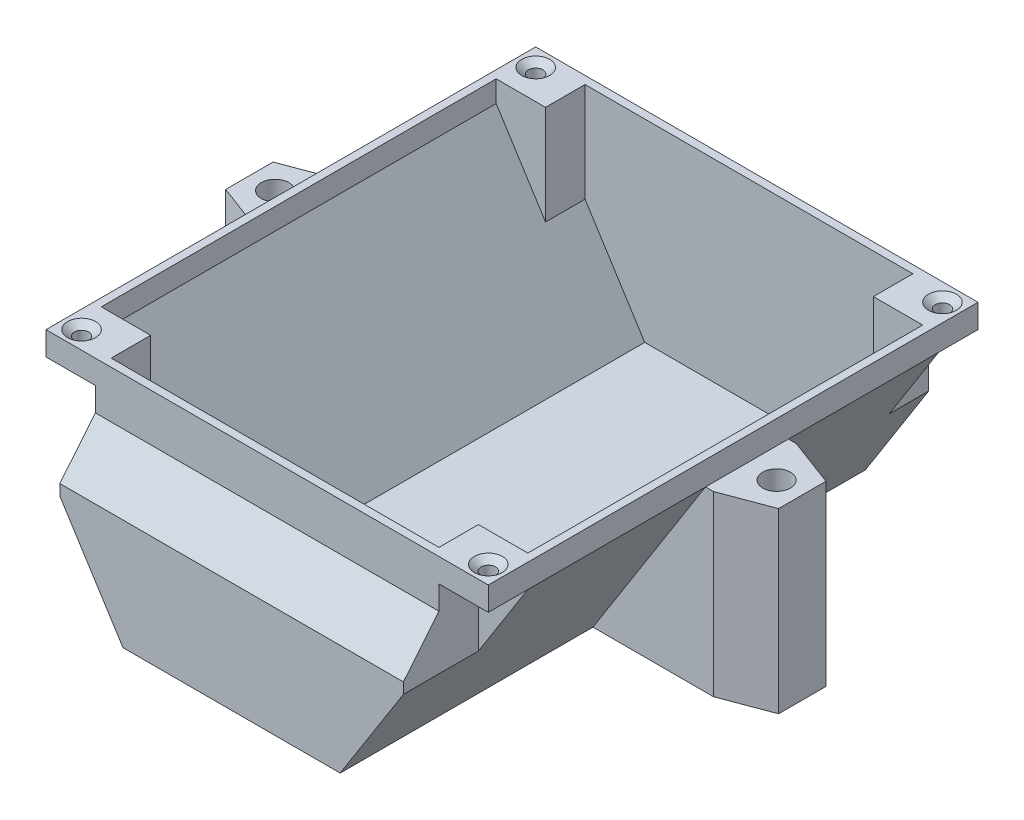
SolidWorks part; units mm, degrees
ref_plane "Front Plane" through (0, 0, 0) normal (0, 0, 1) x (1, 0, 0)
ref_plane "Top Plane" through (0, 0, 0) normal (0, 1, 0) x (1, 0, 0)
ref_plane "Right Plane" through (0, 0, 0) normal (1, 0, 0) x (0, 0, -1)
sketch "Front face" plane through (0, 0, 0) normal (0, 0, 1) x (1, 0, 0)
  line L0 (-28.5, 45) -> (83.5, 45)
  line L1 (0, 0) -> (55, 0)
  line L2 (83.5, 45) -> (55, 0)
  line L3 (-28.5, 45) -> (0, 0)
  line L4 (27.5, 0) -> (27.5, 45) construction
  dimension "D1" = 112
  dimension "D2" = 45
extrude "Main Body" add sketch "Front face" along normal blind 124 contours L2 L1 L3 L0
sketch "Sketch38" plane through (0, 45, 0) normal (0, 1, 0) x (1, 0, 0)
  line L0 (83.5, 0) -> (83.5, -124)
  line L1 (83.5, -124) -> (-28.5, -124)
  line L2 (-28.5, -124) -> (-28.5, 0)
  line L3 (-28.5, 0) -> (83.5, 0)
extrude "Boss-Extrude2" add sketch "Sketch38" along normal blind 6
sketch3d "Reference perpendicular"
  line L1 (0, 0, 0) -> (55, 0, 0) construction
sketch "Sketch22" plane through (0, 51, 0) normal (0, 1, 0) x (1, 0, 0)
  line L0 (-28.5, 0) -> (-16.0038, 0)
  line L1 (-28.5, 0) -> (83.5, 0) construction
  line L2 (-16.0038, 0) -> (-16.0038, -10)
  line L3 (-16.0038, -10) -> (-28.5, -10)
  line L5 (-28.5, -10) -> (-28.5, 0)
  line L6 (-28.5, -62) -> (83.5, -62) construction
  line L9 (27.5, -124) -> (27.5, 0) construction
  line L11 (83.5, -10) -> (83.5, 0)
  line L12 (71.0038, -10) -> (83.5, -10)
  line L13 (71.0038, 0) -> (71.0038, -10)
  line L14 (83.5, 0) -> (71.0038, 0)
  line L15 (83.5, -124) -> (71.0038, -124)
  line L16 (71.0038, -124) -> (71.0038, -114)
  line L17 (71.0038, -114) -> (83.5, -114)
  line L18 (83.5, -114) -> (83.5, -124)
  line L19 (-28.5, -114) -> (-28.5, -124)
  line L20 (-16.0038, -114) -> (-28.5, -114)
  line L21 (-16.0038, -124) -> (-16.0038, -114)
  line L22 (-28.5, -124) -> (-16.0038, -124)
  line L23 (-28.5, 0) -> (-28.5, -124) construction
  line L24 (83.5, -124) -> (83.5, 0) construction
  line L25 (-28.5, -124) -> (83.5, -124) construction
  point P8 (-28.5, -62)
  point P12 (83.5, -62)
  point P17 (27.5, 0)
  point P18 (27.5, -124)
extrude "Screw Cut" cut sketch "Sketch22" against normal up to next
sketch "Sketch23" plane through (0, 0, 0) normal (-1, 0, 0) x (0, 0, 1)
  line L0 (124, 0) -> (124, 39)
  line L2 (124, 25.2692) -> (124, 51) construction
  line L3 (124, 0) -> (133.0015, 0)
  line L4 (133.0015, 0) -> (133.0015, 28)
  line L5 (133.0015, 28) -> (124, 39)
  dimension "D1" = 28
extrude "Box Extension" add sketch "Sketch23" against normal up to vertex and the other way up to vertex
sketch "Sketch28" plane through (0, 0, 124) normal (0, 0, -1) x (-1, 0, 0)
  line L0 (-71.0038, 0) -> (-55, 0)
  line L1 (-55, 0) -> (-71.0038, 25.2692)
  line L2 (-71.0038, 25.2692) -> (-71.0038, 0)
  line L5 (0, 0) -> (16.0038, 0)
  line L6 (16.0038, 0) -> (16.0038, 25.2692)
  line L7 (16.0038, 25.2692) -> (0, 0)
extrude "Cut-Extrude1" cut sketch "Sketch28" against normal through all
shell "Inner Shell" thickness 2
sketch3d "Mid plane"
  line L0 (-28.5, 45, 0) -> (83.5, 45, 0) construction
  dimension "D1" = 48
sketch "Support" plane through (0, 0, 48) normal (0, 0, -1) x (-1, 0, 0)
  line L0 (0, 0) -> (28.5, 0)
  line L1 (28.5, 0) -> (28.5, 45)
  line L2 (28.5, 45) -> (0, 0)
  line L3 (-83.5, 45) -> (-55, 0) construction
  line L7 (-83.5, 45) -> (-55, 0)
  line L8 (-83.5, 0) -> (-83.5, 45)
  line L9 (-55, 0) -> (-83.5, 0)
  point P2 (28.5, 45)
  point P3 (28.5, 45)
extrude "Angle supports" add sketch "Support" against normal blind 21
sketch "Sketch9" plane through (0, 0, 0) normal (0, -1, 0) x (1, 0, 0)
  line L0 (85.5, 69) -> (97.5, 64.5)
  line L1 (85.5, 69) -> (85.5, 48)
  line L3 (83.5, 58.5) -> (97.5, 58.5) construction
  line L4 (97.5, 64.5) -> (97.5, 52.5)
  line L5 (85.5, 48) -> (97.5, 52.5)
  line L6 (27.5, 124) -> (27.5, 0) construction
  line L7 (0, 124) -> (55, 124) construction
  line L8 (85.5, 69) -> (97.5, 64.5)
  line L9 (85.5, 48) -> (97.5, 52.5)
  line L10 (85.5, 69) -> (97.5, 64.5)
  line L11 (85.5, 48) -> (97.5, 52.5)
  line L12 (85.5, 69) -> (97.5, 64.5)
  line L13 (85.5, 48) -> (97.5, 52.5)
  line L14 (-30.5, 48) -> (-42.5, 52.5)
  line L15 (-30.5, 69) -> (-30.5, 48)
  line L16 (-30.5, 69) -> (-42.5, 64.5)
  line L17 (-42.5, 64.5) -> (-42.5, 52.5)
  line L18 (85.5, 69) -> (83.5, 69)
  line L19 (83.5, 69) -> (83.5, 48)
  line L20 (83.5, 48) -> (85.5, 48)
  line L21 (-28.5, 48) -> (-30.5, 48)
  line L22 (-28.5, 69) -> (-28.5, 48)
  line L23 (-30.5, 69) -> (-28.5, 69)
  circle A0 centre (91, 58.5) radius 3.5
  circle A1 centre (-36, 58.5) radius 3.5
  point P2 (85.5373, 48)
  point P3 (88.3856, 48)
  point P21 (0, 0)
  point P24 (85.5, 58.5)
  point P25 (83.5, 69)
  point P26 (0, 0)
  point P27 (83.5, 69)
  point P28 (83.5, 48)
  point P29 (86.7423, 48)
  point P30 (0, 0)
  point P31 (83.5, 48)
  point P32 (0, 0)
  point P33 (0, 0)
  point P34 (90.2479, 58.5)
  point P35 (85.5, 58.5)
  point P36 (83.5, 58.5)
  dimension "D1" = 12
  dimension "D6" = 7
  dimension "D2" = 48
  dimension "D3" = 5.5
  dimension "D4" = 12
  dimension "D5" = 2
  dimension "D7" = 21
extrude "Screw Support" add sketch "Sketch9" against normal up to vertex (51 mm away)
sketch "Sketch14" plane through (0, 51, 0) normal (0, 1, 0) x (1, 0, 0)
  line L0 (27.5, 0) -> (27.5, -124) construction
  line L1 (-28.5, 0) -> (-16.0038, 0)
  line L2 (-28.5, 0) -> (-28.5, -10)
  line L3 (-28.5, -10) -> (-16.0038, -10)
  line L4 (-16.0038, 0) -> (-16.0038, -10)
  line L7 (-26.5, -62) -> (83.5, -62) construction
  line L8 (-26.5, -112) -> (-26.5, -12) construction
  line L10 (71.0038, 0) -> (71.0038, -10)
  line L11 (83.5, -10) -> (71.0038, -10)
  line L12 (83.5, 0) -> (83.5, -10)
  line L13 (83.5, 0) -> (71.0038, 0)
  line L14 (83.5, -124) -> (71.0038, -124)
  line L15 (83.5, -124) -> (83.5, -114)
  line L16 (83.5, -114) -> (71.0038, -114)
  line L17 (71.0038, -124) -> (71.0038, -114)
  line L18 (-16.0038, -124) -> (-16.0038, -114)
  line L19 (-28.5, -114) -> (-16.0038, -114)
  line L20 (-28.5, -124) -> (-28.5, -114)
  line L21 (-28.5, -124) -> (-16.0038, -124)
  line L22 (-16.0038, -124) -> (71.0038, -124) construction
  line L23 (71.0038, 0) -> (-16.0038, 0) construction
  line L24 (83.5, -114) -> (83.5, -10) construction
  point P4 (71.0038, -123)
  point P7 (27.5, 0)
  point P9 (27.5, -124)
  point P13 (-26.5, -62)
  point P16 (81.5, -62)
  point P29 (82.662, -123)
  point P30 (83.5, -113)
  point P31 (0, 0)
  point P32 (-26.1326, -61.5)
  point P33 (81.1326, -61.5)
  point P34 (0, 0)
  point P35 (83.5, -62)
  point P37 (27.5, -2)
  point P39 (0, 0)
  point P42 (-26.5, -62)
extrude "Box Screw support" add sketch "Sketch14" against normal blind 6 contours L20 L19 L18 L21
sketch "Sketch34" plane through (28.068, 51, 0) normal (0, -1, 0) x (1, 0, 0)
  line L0 (-52.068, 119.5) -> (-56.568, 119.5) construction
  line L1 (-56.568, 124) -> (-56.568, 114) construction
  line L3 (-52.068, 124) -> (-52.068, 119.5) construction
  dimension "D1" = 4.5
  dimension "D2" = 4.5
hole_wizard "CSK for #6 Flat Head Machine Screw (100)3" positions "3DSketch3" profile "Sketch35" countersink size "#6" standard "ANSI Inch" end condition through all
sketch3d "3DSketch3"
  point P0 (-24, 51, 119.5)
sketch "Sketch35" plane through (-24, 51, 119.5) normal (1, 0, 0) x (0, 0, 1)
  line L0 (0, 0) -> (0, 51)
  line L1 (0, 51) -> (1.8288, 51)
  line L2 (1.8288, 51) -> (1.8288, 1.4386)
  line L3 (1.8288, 1.4386) -> (3.5433, 0)
  line L5 (3.5433, 0) -> (0, 0)
  line L6 (-1.8288, 1.4386) -> (-3.5433, 0) construction
  line L11 (0, -6.35) -> (0, 107.95) construction
  dimension "Thru Hole Dia." = 3.6576
  dimension "Thru Hole Depth" = 51
  dimension "Near C'Sink Dia." = 7.0866
  dimension "Near C'Sink Angle" = 100
pattern_linear "LPattern1" count 2 spacing 103 along (1, 0, 0) count 2 spacing 115 along (0, 0, -1) of "CSK for #6 Flat Head Machine Screw (100)3"
fillet "Fillet1" [suppressed] radius 4.5
fillet "Fillet2" [suppressed] radius 2
fillet "Fillet3" [suppressed] radius 2
